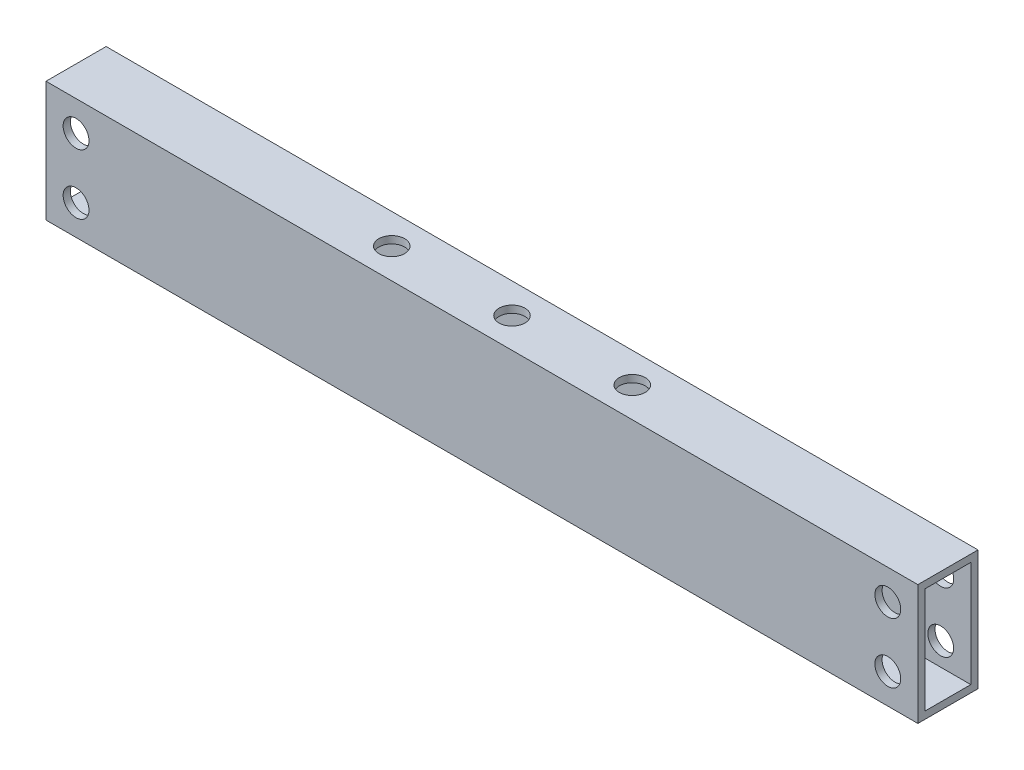
SolidWorks part; units mm, degrees
material "5052-H34"
ref_plane "正面" through (0, 0, 0) normal (0, 0, 1) x (1, 0, 0)
ref_plane "平面" through (0, 0, 0) normal (0, 1, 0) x (1, 0, 0)
ref_plane "右側面" through (0, 0, 0) normal (1, 0, 0) x (0, 0, -1)
sketch "ｽｹｯﾁ1" plane through (0, 0, 0) normal (1, 0, 0) x (0, 0, -1)
  line L1 (-5, 10) -> (5, 10)
  line L2 (-5, 10) -> (-5, -10)
  line L3 (-5, -10) -> (5, -10)
  line L4 (5, 10) -> (5, -10)
  line L5 (-5, 10) -> (5, -10) construction
  line L6 (-5, -10) -> (5, 10) construction
  point P0 (0, 0)
  dimension "D1" = 10
  dimension "D2" = 20
extrude "押し出し-薄板1" add sketch "ｽｹｯﾁ1" along normal blind 145 thin
sketch "ｽｹｯﾁ3" plane through (0, 10, 0) normal (0, 1, 0) x (1, 0, 0)
  line L0 (72.5, 5) -> (72.5, -5) construction
  line L1 (145, 5) -> (0, 5) construction
  line L2 (145, -5) -> (0, -5) construction
  line L3 (72.5, 0) -> (92.5, 0) construction
  circle A0 centre (92.5, 0) radius 2.15
  circle A1 centre (52.5, 0) radius 2.15
  circle A2 centre (72.5, 0) radius 2.15
  dimension "D1" = 4.3
  dimension "D2" = 40
extrude "ｶｯﾄ - 押し出し1" cut sketch "ｽｹｯﾁ3" against normal through all
sketch "ｽｹｯﾁ4" plane through (0, 0, 5) normal (0, 0, 1) x (1, 0, 0)
  line L0 (72.5, 10) -> (72.5, -10) construction
  line L1 (145, 10) -> (0, 10) construction
  line L2 (145, -10) -> (0, -10) construction
  line L3 (72.5, 0) -> (140, 0) construction
  line L4 (140, 0) -> (140, 5) construction
  line L5 (145, 10) -> (145, -10) construction
  circle A0 centre (140, 5) radius 2.15
  circle A1 centre (140, -5) radius 2.15
  circle A2 centre (5, 5) radius 2.15
  circle A3 centre (5, -5) radius 2.15
  dimension "D1" = 4.3
  dimension "D2" = 10
  dimension "D3" = 5
extrude "ｶｯﾄ - 押し出し2" cut sketch "ｽｹｯﾁ4" against normal through all
